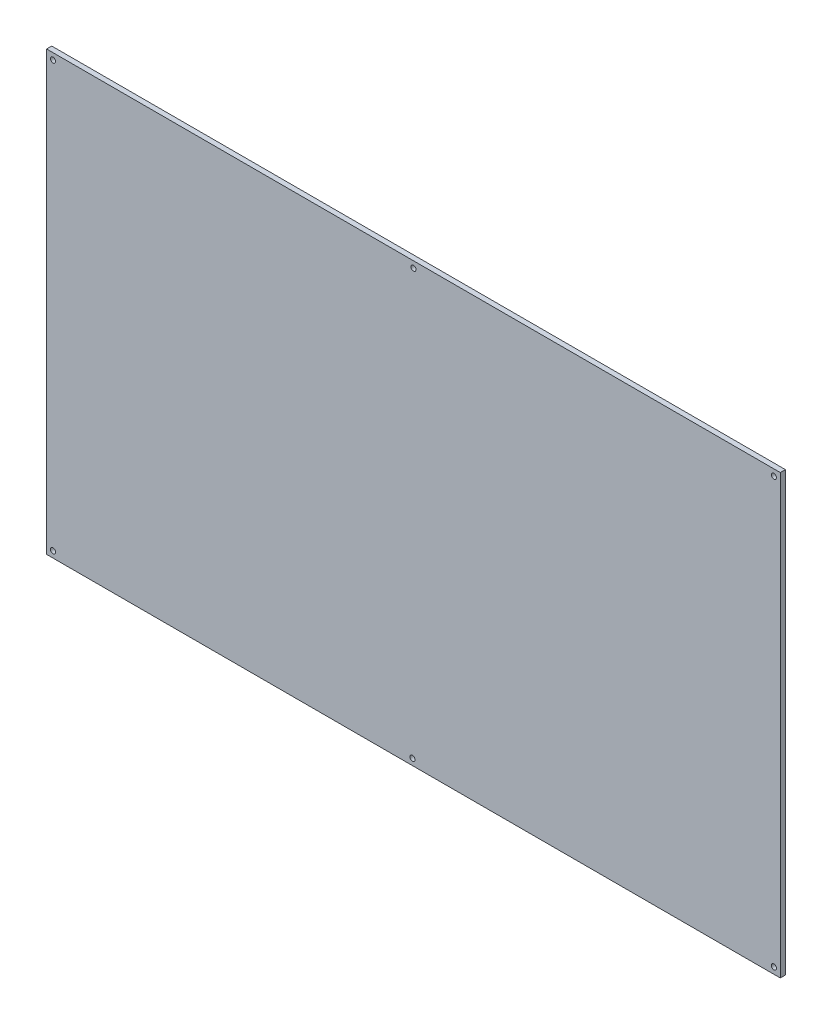
SolidWorks part; units mm, degrees
ref_plane "Plan de face" through (0, 0, 0) normal (0, 0, 1) x (1, 0, 0)
ref_plane "Plan de dessus" through (0, 0, 0) normal (0, 1, 0) x (1, 0, 0)
ref_plane "Plan de droite" through (0, 0, 0) normal (1, 0, 0) x (0, 0, -1)
sketch "Esquisse1" plane through (0, 0, 0) normal (0, 0, 1) x (1, 0, 0)
  line L1 (-43.7735, 19.486) -> (243.0265, 19.486)
  line L2 (-43.7735, 19.486) -> (-43.7735, -151.624)
  line L3 (-43.7735, -151.624) -> (243.0265, -151.624)
  line L4 (243.0265, 19.486) -> (243.0265, -151.624)
  circle A0 centre (-41.2735, 16.986) radius 1
  circle A1 centre (-41.2735, -149.124) radius 1
  circle A2 centre (240.5265, 16.986) radius 1
  circle A3 centre (240.5265, -149.124) radius 1
  circle A4 centre (99.6265, 16.986) radius 1
  circle A5 centre (99.2441, -149.124) radius 1
  dimension "D3" = 2.5
  dimension "D11" = 143.4
  dimension "D1" = 286.8
  dimension "D2" = 171.11
  dimension "D4" = 2.5
  dimension "D5" = 2.5
  dimension "D6" = 2.5
  dimension "D7" = 2.5
  dimension "D8" = 2.5
  dimension "D9" = 2.5
  dimension "D10" = 2.5
extrude "Boss.-Extru.1" add sketch "Esquisse1" along normal blind 2
